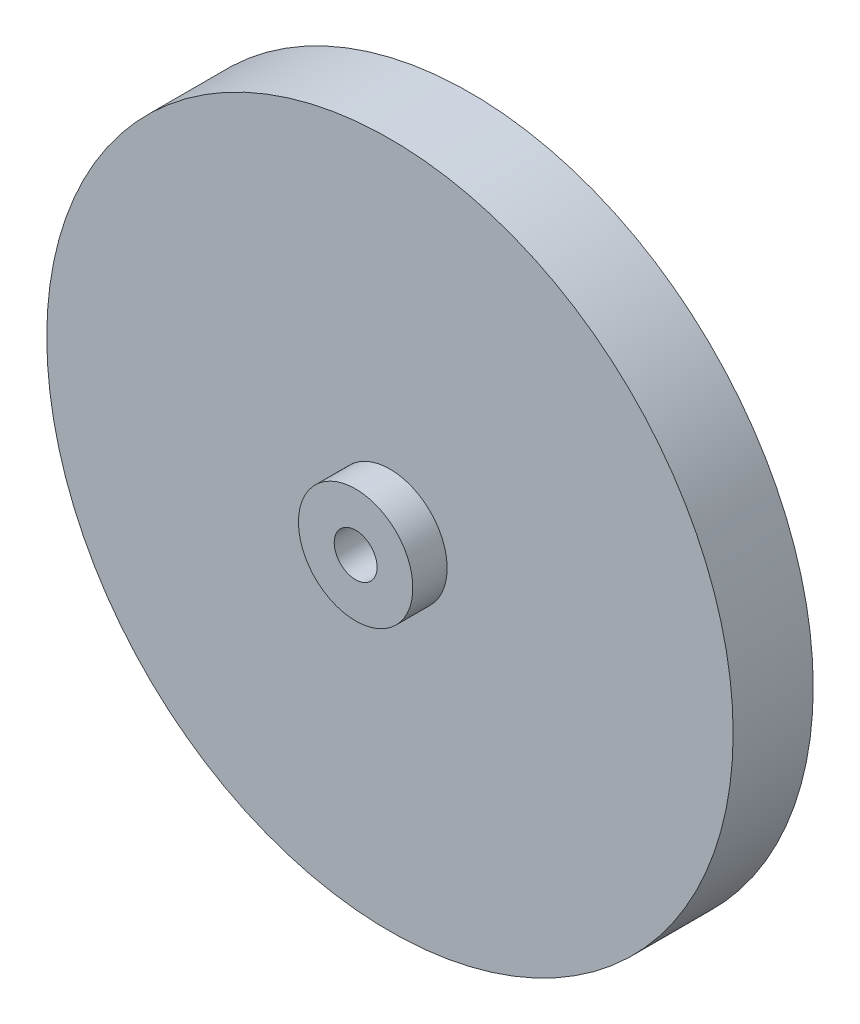
SolidWorks part; units mm, degrees
material "AISI 1020"
ref_plane "Front Plane" through (0, 0, 0) normal (0, 0, 1) x (1, 0, 0)
ref_plane "Top Plane" through (0, 0, 0) normal (0, 1, 0) x (1, 0, 0)
ref_plane "Right Plane" through (0, 0, 0) normal (1, 0, 0) x (0, 0, -1)
sketch "Sketch1" plane through (0, 0, 0) normal (0, 1, 0) x (1, 0, 0)
  line L0 (0, 56.2011) -> (0, -37.3336) construction
  line L1 (-3.75, 40.4948) -> (-10, 40.4948)
  line L2 (-10, 40.4948) -> (-60, 40.4948)
  line L4 (-60, 40.4948) -> (-60, 26.4948)
  line L5 (-60, 26.4948) -> (-10, 26.4948)
  line L6 (-10, 26.4948) -> (-10, 20.4948)
  line L7 (-10, 20.4948) -> (-3.75, 20.4948)
  line L8 (-3.75, 40.4948) -> (-3.75, 20.4948)
  dimension "D1" = 10
  dimension "D2" = 3.75
  dimension "D3" = 60
  dimension "D4" = 6
  dimension "D5" = 14
  dimension "D6" = 20
revolve "Revolve1" add sketch "Sketch1" angle 360 about L0
